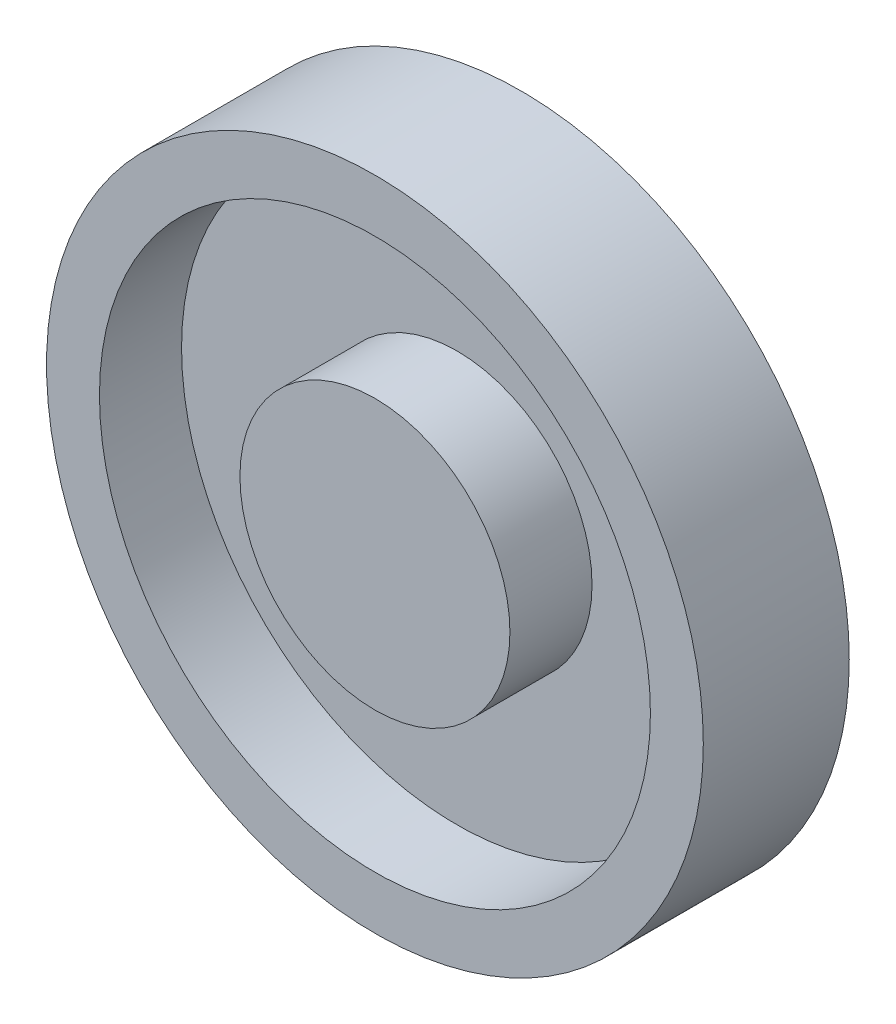
SolidWorks part; units mm, degrees
ref_plane "Front Plane" through (0, 0, 0) normal (0, 0, 1) x (1, 0, 0)
ref_plane "Top Plane" through (0, 0, 0) normal (0, 1, 0) x (1, 0, 0)
ref_plane "Right Plane" through (0, 0, 0) normal (1, 0, 0) x (0, 0, -1)
sketch "Sketch1" plane through (0, 0, 0) normal (0, 0, 1) x (1, 0, 0)
  circle A0 centre (0, 0) radius 18
  dimension "D1" = 36
extrude "Boss-Extrude1" add sketch "Sketch1" along normal blind 8
sketch "Sketch2" plane through (0, 0, 8) normal (0, 0, 1) x (1, 0, 0)
  circle A0 centre (0, 0) radius 7.4
  circle A1 centre (0, 0) radius 15.1
  dimension "D1" = 30.2
  dimension "D2" = 14.8
extrude "Cut-Extrude1" cut sketch "Sketch2" against normal blind 4.5
